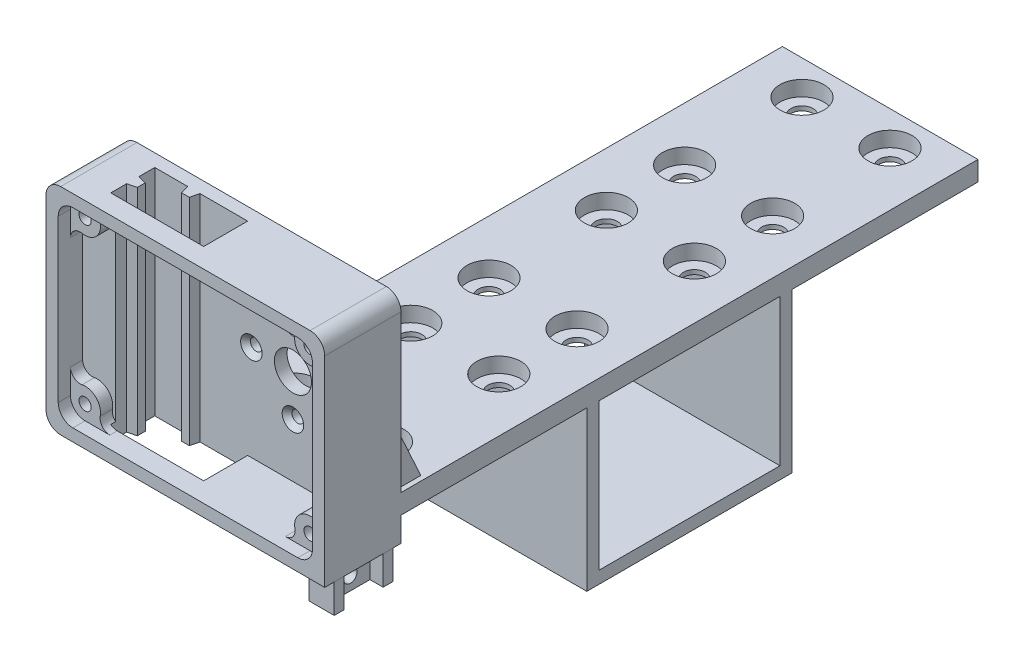
SolidWorks part; units mm, degrees
other "Markup1"
sketch "Sketch26" plane through (0, -41.85, 15.6) normal (0.2159, -0.9515, 0.2193) x (0.5478, -0.0679, -0.8339)
ref_plane "Front Plane" through (0, 0, 0) normal (0, 0, 1) x (1, 0, 0)
ref_plane "Top Plane" through (0, 0, 0) normal (0, 1, 0) x (1, 0, 0)
ref_plane "Right Plane" through (0, 0, 0) normal (1, 0, 0) x (0, 0, -1)
sketch "Sketch1" plane through (0, 0, 0) normal (1, 0, 0) x (0, 0, -1)
  line L5 (0, 0) -> (118, 0)
  line L6 (0, 0) -> (0, -4)
  line L8 (118, 0) -> (118, -4)
  line L13 (80, -4) -> (80, -36.5)
  line L14 (80, -36.5) -> (38, -36.5)
  line L15 (38, -36.5) -> (38, -4)
  line L17 (38, -4) -> (0, -4)
  line L18 (80, -4) -> (118, -4)
  line L19 (59, -36.5) -> (59, 0) construction
  line L20 (59, -4) -> (59, -34) construction
  line L25 (40.5, -4) -> (77.5, -4)
  line L26 (40.5, -4) -> (40.5, -34)
  line L27 (40.5, -34) -> (77.5, -34)
  line L28 (77.5, -4) -> (77.5, -34)
  line L29 (40.5, -19) -> (77.5, -19) construction
  dimension "D11" = 4
  dimension "D1" = 38
  dimension "D2" = 42
  dimension "D3" = 38
  dimension "D4" = 4
  dimension "D5" = 4
  dimension "D6" = 37
  dimension "D7" = 30
  dimension "D8" = 32.5
extrude "Boss-Extrude1" add sketch "Sketch1" against normal blind 40
sketch "Sketch2" plane through (0, 0, 0) normal (0, 1, 0) x (1, 0, 0)
  line L0 (-20, 116) -> (-20, 82) construction
  line L5 (-35, 19) -> (-5, 19) construction
  line L6 (-5, 36) -> (-35, 2) construction
  line L7 (-5, 116) -> (-35, 116)
  line L8 (-5, 116) -> (-5, 82)
  line L9 (-5, 82) -> (-35, 82)
  line L10 (-35, 116) -> (-35, 82)
  line L11 (-5, 116) -> (-35, 82) construction
  line L12 (-5, 82) -> (-35, 116) construction
  line L13 (-5, 76.5) -> (-35, 76.5)
  line L14 (-5, 76.5) -> (-5, 41.5)
  line L15 (-5, 41.5) -> (-35, 41.5)
  line L16 (-35, 76.5) -> (-35, 41.5)
  line L17 (-5, 76.5) -> (-35, 41.5) construction
  line L18 (-5, 41.5) -> (-35, 76.5) construction
  line L19 (-5, 2) -> (-35, 36) construction
  line L20 (-40, 0) -> (0, 0) construction
  line L21 (-40, 118) -> (0, 118) construction
  line L22 (-40, 118) -> (-40, 0) construction
  line L23 (-20, 41.5) -> (-20, 76.5) construction
  line L24 (-35, 59) -> (-5, 59) construction
  line L25 (-35, 99) -> (-5, 99) construction
  line L26 (-20, 2) -> (-20, 36) construction
  line L27 (-35, 2) -> (-35, 36)
  line L28 (-5, 36) -> (-35, 36)
  line L29 (-5, 2) -> (-5, 36)
  line L30 (-5, 2) -> (-35, 2)
  point P5 (-20, 99)
  point P10 (-20, 59)
  point P18 (-40, 59)
  point P22 (-20, 0)
  point P25 (-20, 118)
  point P29 (-11, 87)
  point P33 (-11, 111)
  point P35 (-29, 111)
  point P36 (-29, 87)
  point P40 (-29, 31)
  point P41 (-29, 7)
  point P42 (-11, 7)
  point P43 (-11, 31)
  point P44 (-20, 19)
  point P45 (-11, 71)
  point P46 (-11, 47)
  point P49 (-29, 47)
  point P50 (-29, 71)
  dimension "D1" = 35
  dimension "D2" = 30
  dimension "D3" = 5.5
  dimension "D4" = 40
  dimension "D5" = 34
  dimension "D6" = 30
  dimension "D7" = 6
  dimension "D9" = 12
  dimension "D10" = 9
sketch "Sketch3" plane through (0, 0, 0) normal (1, 0, 0) x (0, 0, -1)
  line L0 (40.5, -4) -> (77.5, -34) construction
  line L1 (77.5, -4) -> (40.5, -34) construction
  point P8 (59, -19)
hole_wizard "CBORE for M4 Pan Head Machine Screw1" positions "3DSketch1" profile "Sketch4" counterbore size "M4" standard "ANSI Metric"
sketch3d "3DSketch1"
  point P0 (-11, 0, -111)
  point P3 (-29, 0, -111)
  point P6 (-11, 0, -87)
  point P9 (-29, 0, -87)
  point P12 (-11, 0, -71)
  point P15 (-11, 0, -47)
  point P18 (-29, 0, -47)
  point P21 (-29, 0, -71)
  point P24 (-11, 0, -31)
  point P27 (-29, 0, -31)
  point P30 (-29, 0, -7)
  point P33 (-11, 0, -7)
sketch "Sketch4" plane through (-11, 0, -111) normal (1, 0, 0) x (0, 0, 1)
  line L0 (0, 0) -> (0, 4)
  line L1 (0, 4) -> (2.25, 4)
  line L3 (2.25, 4) -> (2.25, 3.1)
  line L4 (2.25, 3.1) -> (4.5, 3.1)
  line L5 (4.5, 3.1) -> (4.5, 0)
  line L7 (4.5, 0) -> (0, 0)
  line L11 (0, -6.35) -> (0, 107.95) construction
  dimension "Thru Hole Dia." = 4.5
  dimension "Thru Hole Depth" = 4
  dimension "C'Bore Dia." = 9
  dimension "C'Bore Depth" = 3.1
ref_plane "Plane1" through (-39, 0, 0) normal (1, 0, 0) x (0, 0, -1)
sketch "Sketch5" plane through (-39, 0, 0) normal (1, 0, 0) x (0, 0, -1)
  line L1 (55, -36.5) -> (63, -36.5)
  line L2 (55, -36.5) -> (55, -41.85)
  line L4 (63, -36.5) -> (63, -41.85)
  line L5 (38, -36.5) -> (80, -36.5) construction
  line L6 (63, -41.85) -> (55, -41.85)
  circle A1 centre (59, -39.5) radius 1.35
  point P4 (59, -36.5)
  point P5 (59, -36.5)
  dimension "D3" = 2.7
  dimension "D2" = 3
  dimension "D1" = 8
  dimension "D4" = 5.35
extrude "Boss-Extrude2" add sketch "Sketch5" along normal blind 3
ref_plane "Plane2" through (-28, 0, 0) normal (1, 0, 0) x (0, 0, -1)
sketch "Sketch6" plane through (-28, 0, 0) normal (1, 0, 0) x (0, 0, -1)
  line L3 (55, -36.5) -> (55, -41.85)
  line L4 (63, -41.85) -> (63, -36.5)
  line L5 (63, -36.5) -> (55, -36.5)
  line L6 (55, -36.5) -> (55, -41.85)
  line L7 (63, -41.85) -> (63, -36.5)
  line L8 (63, -36.5) -> (55, -36.5)
  line L10 (55, -41.85) -> (63, -41.85)
  line L11 (55, -41.85) -> (63, -41.85)
  circle A0 centre (59, -39.5) radius 1.35 construction
  circle A3 centre (59, -39.5) radius 1.35
  dimension "D1" = 0
extrude "Boss-Extrude3" add sketch "Sketch6" along normal blind 6
sketch "Sketch7" plane through (-28, 0, 0) normal (-1, 0, 0) x (0, 0, 1)
  line L1 (-63, -38.5) -> (-62.2, -38.5)
  line L2 (-63, -38.5) -> (-63, -40.9)
  line L3 (-63, -40.9) -> (-62.2, -40.9)
  line L4 (-62.2, -38.5) -> (-62.2, -40.9)
  line L6 (-55, -40.9) -> (-55.8, -40.9)
  line L7 (-55, -38.5) -> (-55.8, -38.5)
  line L8 (-55.8, -38.5) -> (-55.8, -40.9)
  line L9 (-55, -38.5) -> (-55, -40.9)
  line L10 (-55, -36.5) -> (-55, -41.85) construction
  line L11 (-63, -36.5) -> (-55, -36.5) construction
  line L12 (-63, -41.85) -> (-63, -36.5) construction
  dimension "D1" = 0.8
  dimension "D2" = 0.8
  dimension "D3" = 2.4
  dimension "D4" = 2.4
  dimension "D5" = 2
  dimension "D6" = 2
  dimension "D7" = 0.8
extrude "Boss-Extrude4" add sketch "Sketch7" along normal up to next
sketch "Sketch8" plane through (-36, 0, 0) normal (1, 0, 0) x (0, 0, -1)
  line L0 (63, -41.85) -> (63, -40.9) construction
  line L1 (63, -38.5) -> (62.2, -38.5)
  line L2 (63, -38.5) -> (63, -40.9)
  line L3 (63, -40.9) -> (62.2, -40.9)
  line L4 (62.2, -38.5) -> (62.2, -40.9)
  line L5 (63, -36.5) -> (55, -36.5) construction
  line L6 (55, -36.5) -> (55, -38.5) construction
  line L7 (55, -38.5) -> (55.8, -38.5)
  line L8 (55, -38.5) -> (55, -40.9)
  line L9 (55, -40.9) -> (55.8, -40.9)
  line L10 (55.8, -38.5) -> (55.8, -40.9)
  dimension "D1" = 0.8
  dimension "D2" = 2
  dimension "D3" = 2.4
  dimension "D4" = 0.8
  dimension "D5" = 2
  dimension "D6" = 2.4
ref_plane "Plane3" through (0, 0, 0) normal (0, 1, 0) x (1, 0, 0)
sketch "Sketch9" plane through (0, 0, 0) normal (0, 1, 0) x (1, 0, 0)
  line L0 (0, 40.5) -> (0, 77.5) construction
  line L1 (0, 0) -> (-57, 0)
  line L2 (0, 0) -> (0, -2.6)
  line L3 (0, -2.6) -> (-57, -2.6)
  line L4 (-57, 0) -> (-57, -2.6)
  dimension "D1" = 57
  dimension "D2" = 2.6
extrude "Boss-Extrude6" add sketch "Sketch9" along normal blind 35 and the other way blind 9
extrude "Boss-Extrude5" add sketch "Sketch8" along normal blind 2
ref_plane "Plane4" through (-37, 0, 0) normal (-1, 0, 0) x (0, 0, 1)
sketch "Sketch11" plane through (-37, 0, 0) normal (-1, 0, 0) x (0, 0, 1)
  line L0 (-0.0362, 10.9547) -> (-5.0362, 0.046)
  line L1 (22, 0) -> (-22, 0) construction
  line L2 (0, -9) -> (0, 35) construction
  line L4 (-0.0362, 10.9547) -> (-0.0362, 0.046) construction
  line L5 (-0.0362, 0.046) -> (-5.0362, 0.046) construction
  point P1 (-0.0362, 4.9009)
  point P2 (-0.0362, 10.5756)
  dimension "D1" = 12
  dimension "D2" = 5
  dimension "D3" = 0.046
  dimension "D4" = 0.0362
rib "Rib2" sketch "Sketch11" sketch "Sketch11" thickness 2 extrusion direction parallel to sketch draft on no parameters "D1"=2
ref_plane "Plane5" through (-2, 0, 0) normal (1, 0, 0) x (0, 0, -1)
sketch "Sketch12" plane through (-2, 0, 0) normal (1, 0, 0) x (0, 0, -1)
  line L0 (0.0362, 10.9547) -> (5.0362, 0.046) construction
  line L1 (0.0362, 10.9547) -> (5.0362, 0.046)
rib "Rib3" sketch "Sketch12" sketch "Sketch12" thickness 2 extrusion direction parallel to sketch draft on no parameters "D1"=2
sketch "Sketch13" plane through (0, 0, 0) normal (0, 0, -1) x (-1, 0, 0)
  line L0 (19.5, 0) -> (19.5, 35) construction
  line L1 (36, 0) -> (3, 0) construction
  line L3 (0, 35) -> (57, 35) construction
  circle A0 centre (19.5, 13) radius 3.8
  point P7 (19.5, 13)
  dimension "D2" = 7.6
  dimension "D1" = 13
extrude "Cut-Extrude1" cut sketch "Sketch13" against normal up to next
sketch "Sketch14" plane through (0, 0, 2.6) normal (0, 0, 1) x (1, 0, 0)
  line L4 (-57, -9) -> (0, -9)
  line L5 (0, -9) -> (0, 35)
  line L6 (0, 35) -> (-57, 35)
  line L7 (-57, 35) -> (-57, -9)
  line L8 (-57, -9) -> (0, -9)
  line L9 (0, -9) -> (0, 35)
  line L10 (0, 35) -> (-57, 35)
  line L11 (-57, 35) -> (-57, -9)
  dimension "D1" = 0
extrude "Boss-Extrude7" add sketch "Sketch14" along normal blind 13
sketch3d "3DSketch3"
  line L0 (-2.5, -6.5, 15.6) -> (-2.5, 32.5, 15.6)
  line L1 (-2.5, 32.5, 15.6) -> (-54.5, 32.5, 15.6)
  line L2 (-54.5, 32.5, 15.6) -> (-54.5, -6.5, 15.6)
  line L3 (-54.5, -6.5, 15.6) -> (-2.5, -6.5, 15.6)
  line L4 (-2.5, -6.5, 15.6) -> (-2.5, 32.5, 15.6)
  line L5 (-2.5, 32.5, 15.6) -> (-54.5, 32.5, 15.6)
  line L6 (-54.5, 32.5, 15.6) -> (-54.5, -6.5, 15.6)
  line L7 (-54.5, -6.5, 15.6) -> (-2.5, -6.5, 15.6)
  dimension "D1" = 2.5
extrude "Cut-Extrude2" cut sketch "3DSketch3" along direction (0, 0, 1) on the side against the normal blind 13 contours L4 L5 L6 L7
fillet "Fillet3" radius 3 7 edges at (-57, -9, 7.8) (0, 35, 7.8) (-57, 35, 7.8)
sketch "Sketch15" plane through (0, 35, 0) normal (0, 1, 0) x (1, 0, 0)
  line L20 (-31.7575, -2.6) -> (-38.2575, -2.6)
  line L21 (-38.2575, -2.6) -> (-38.7575, -4.6)
  line L22 (-38.7575, -4.6) -> (-40.7575, -4.6)
  line L23 (-40.7575, -4.6) -> (-41.2575, -2.6)
  line L24 (-41.2575, -2.6) -> (-47.7575, -2.6)
  line L25 (-47.7575, -2.6) -> (-47.7575, -5.6)
  line L26 (-47.7575, -5.6) -> (-45.7575, -6.1)
  line L27 (-45.7575, -6.1) -> (-45.7575, -8.1)
  line L28 (-45.7575, -8.1) -> (-47.7575, -8.6)
  line L29 (-47.7575, -8.6) -> (-47.7575, -10.93)
  line L30 (-47.7575, -10.93) -> (-31.7575, -10.93)
  line L31 (-31.7575, -10.93) -> (-31.7575, -2.6)
  line L32 (-31.7575, -2.6) -> (-38.2575, -2.6) construction
  line L33 (-38.2575, -2.6) -> (-38.7575, -4.6) construction
  line L34 (-38.7575, -4.6) -> (-40.7575, -4.6) construction
  line L35 (-40.7575, -4.6) -> (-41.2575, -2.6) construction
  line L36 (-41.2575, -2.6) -> (-47.7575, -2.6) construction
  line L37 (-47.7575, -2.6) -> (-47.7575, -5.6) construction
  line L38 (-47.7575, -5.6) -> (-45.7575, -6.1) construction
  line L39 (-45.7575, -6.1) -> (-45.7575, -8.1) construction
  line L40 (-45.7575, -8.1) -> (-47.7575, -8.6) construction
  line L41 (-47.7575, -8.6) -> (-47.7575, -10.93) construction
  line L42 (-47.7575, -10.93) -> (-31.7575, -10.93) construction
  line L43 (-31.7575, -10.93) -> (-31.7575, -2.6) construction
  dimension "D2" = 0
sketch3d "3DSketch4"
  line L0 (-54.5, 29.5, 2.6) -> (-54.5, -3.5, 2.6) construction
  line L1 (-54.5, 29.5, 2.6) -> (-54.5, -3.5, 2.6)
  line L2 (-51.5, 32.5, 2.6) -> (-38.5, 32.5, 2.6)
  line L3 (-38.5, 32.5, 2.6) -> (-38.5, -6.5, 2.6)
  line L4 (-38.5, -6.5, 2.6) -> (-51.5, -6.5, 2.6)
  arc A0 (-54.5, -3.5, 2.6) -> (-51.5, -6.5, 2.6) centre (-51.5, -3.5, 2.6) ccw construction
  arc A1 (-51.5, 32.5, 2.6) -> (-54.5, 29.5, 2.6) centre (-51.5, 29.5, 2.6) ccw construction
  arc A2 (-54.5, -3.5, 2.6) -> (-51.5, -6.5, 2.6) centre (-51.5, -3.5, 2.6) ccw
  arc A3 (-51.5, 32.5, 2.6) -> (-54.5, 29.5, 2.6) centre (-51.5, 29.5, 2.6) ccw
  point P3 (-51.5, -3.5, 5.6)
  point P5 (-51.5, -3.5, 5.6)
  point P8 (-51.5, 29.5, 5.6)
  point P9 (-51.5, 29.5, 5.6)
  dimension "D1" = 13
extrude "Boss-Extrude8" add sketch "3DSketch4" along direction (0, 0, -1) on the side of the normal blind 8 contours A2 L1 A3 L2 L3 L4
sketch "Sketch16" plane through (0, 35, 0) normal (0, 1, 0) x (1, 0, 0)
  line L0 (-41.2575, -2.6) -> (-47.7575, -2.6)
  line L1 (-47.7575, -2.6) -> (-47.7575, -5.85)
  line L2 (-47.7575, -5.85) -> (-46.0075, -6.2875)
  line L3 (-46.0075, -6.2875) -> (-46.0075, -7.9125)
  line L4 (-46.0075, -7.9125) -> (-47.7575, -8.35)
  line L5 (-47.7575, -8.35) -> (-47.7575, -11.6)
  line L6 (-47.7575, -11.6) -> (-28.7575, -11.6)
  line L7 (-28.7575, -11.6) -> (-28.7575, -2.6)
  line L8 (-28.7575, -2.6) -> (-38.5075, -2.6)
  line L9 (-38.5075, -2.6) -> (-38.945, -4.35)
  line L10 (-38.945, -4.35) -> (-40.57, -4.35)
  line L11 (-40.57, -4.35) -> (-41.0075, -2.6)
  line L12 (-41.0075, -2.6) -> (-41.2575, -2.6)
  line L13 (-3, 0) -> (-54, 0) construction
  line L14 (-47.7575, -8.6) -> (-47.7575, -10.93) construction
  line L17 (-45.7575, -8.1) -> (-47.7575, -8.6) construction
  line L19 (-45.7575, -6.1) -> (-45.7575, -8.1) construction
  line L21 (-38.2575, -2.6) -> (-38.7575, -4.6) construction
  dimension "D1" = 2.6
  dimension "D2" = 9
  dimension "D3" = 19
  dimension "D4" = 0.25
  dimension "D5" = 2.5
  dimension "D6" = 3.25
  dimension "D7" = 0.25
extrude "Cut-Extrude3" cut sketch "Sketch16" against normal up to next
sketch "Sketch17" plane through (0, 0, 2.6) normal (0, 0, 1) x (1, 0, 0)
  line L0 (-11, 13) -> (-28, 13) construction
  line L1 (-19.5, 4.5) -> (-19.5, 21.5) construction
  circle A0 centre (-19.5, 13) radius 3.8 construction
  point P4 (-19.5, 13)
  dimension "D1" = 17
  dimension "D2" = 17
hole_wizard "CSK for M2 Countersunk Flat Head Screw1" positions "Sketch18" profile "Sketch19" countersink size "M2" standard "ISO" end condition up to next
sketch "Sketch18" plane through (0, 0, 2.6) normal (0, 0, 1) x (1, 0, 0)
  point P0 (-19.5, 21.5)
  point P3 (-28, 13)
  point P6 (-19.5, 4.5)
  point P9 (-11, 13)
sketch "Sketch19" plane through (-19.5, 21.5, 2.6) normal (1, 0, 0) x (0, -1, 0)
  line L0 (0, 0) -> (0, 2.6)
  line L1 (0, 2.6) -> (1.2, 2.6)
  line L2 (1.2, 2.6) -> (1.2, 1)
  line L3 (1.2, 1) -> (2.2, 0)
  line L5 (2.2, 0) -> (0, 0)
  line L6 (-1.2, 1) -> (-2.2, 0) construction
  line L11 (0, -6.35) -> (0, 107.95) construction
  dimension "Thru Hole Dia." = 2.4
  dimension "Thru Hole Depth" = 2.6
  dimension "Near C'Sink Dia." = 4.4
  dimension "Near C'Sink Angle" = 90
sketch "Sketch20" plane through (0, 0, 2.6) normal (0, 0, 1) x (1, 0, 0)
  line L1 (-5.5, 32.5) -> (-28.7575, 32.5) construction
  line L2 (-2.5, -3.5) -> (-2.5, 29.5) construction
  line L3 (-6.4777, 32.5) -> (-5.5, 32.5)
  line L4 (-2.5, 28.5223) -> (-2.5, 29.5)
  arc A0 (-5.5, -6.5) -> (-2.5, -3.5) centre (-5.5, -3.5) ccw construction
  arc A1 (-2.5, 29.5) -> (-5.5, 32.5) centre (-5.5, 29.5) ccw construction
  arc A2 (-6.4777, 32.5) -> (-2.5, 28.5223) centre (-5.5, 29.5) ccw
  arc A3 (-2.5, 29.5) -> (-5.5, 32.5) centre (-5.5, 29.5) ccw construction
  arc A4 (-2.5, 29.5) -> (-5.5, 32.5) centre (-5.5, 29.5) ccw
  point P0 (-5.5, 29.5)
  point P1 (-5.5, -3.5)
  dimension "D1" = 3.1553
sketch "Sketch21" plane through (0, 0, 10.6) normal (0, 0, 1) x (1, 0, 0)
  arc A0 (-54.5, -3.5) -> (-51.5, -6.5) centre (-51.5, -3.5) ccw construction
  arc A1 (-51.5, 32.5) -> (-54.5, 29.5) centre (-51.5, 29.5) ccw construction
  point P0 (-51.5, 29.5)
  point P1 (-51.5, -3.5)
  point P2 (0, 0)
  point P6 (0, 0)
extrude "Boss-Extrude9" add sketch "Sketch20" along normal blind 10.5
fillet "Fillet4" radius 2 2 edges at (-2.5, 28.5223, 7.85) (-6.4777, 32.5, 7.85)
sketch "Sketch22" plane through (0, 0, 15.6) normal (0, 0, 1) x (1, 0, 0)
  line L0 (-28.5, -6.5) -> (-28.5, 32.5) construction
  line L2 (-54.5, 13) -> (-2.5, 13) construction
  line L12 (-5.5, 32.5) -> (-51.5, 32.5) construction
  line L13 (-51.5, -6.5) -> (-5.5, -6.5) construction
  line L15 (-54.5, 29.5) -> (-54.5, -3.5) construction
  line L16 (-2.5, -3.5) -> (-2.5, 29.5) construction
  point P2 (0, 0)
  point P3 (0, 0)
  point P4 (0, 0)
  point P7 (0, 0)
  point P8 (0, 0)
  point P9 (0, 0)
  point P10 (0, 0)
  point P11 (0, 0)
  point P12 (-53.1765, 13)
  point P14 (0, 0)
  point P15 (0, 0)
  point P16 (0, 0)
  point P17 (0, 0)
  point P18 (0, 0)
  point P19 (0, 0)
  point P22 (0, 0)
  point P23 (0, 0)
  point P24 (0, 0)
  point P25 (0, 0)
  point P26 (0, 0)
  point P28 (0, 0)
  point P29 (0, 0)
  point P30 (0, 0)
  point P33 (0, 0)
  point P34 (0, 0)
  point P35 (0, 0)
  point P36 (0, 0)
  point P37 (0, 0)
ref_plane "Plane7" through (0, 13, 0) normal (0, -1, 0) x (1, 0, 0)
ref_plane "Plane8" through (-28.5, 0, 0) normal (1, 0, 0) x (0, 0, -1)
mirror "Mirror1" about plane through (-28.5, 0, 0) normal (1, 0, 0) of "Boss-Extrude9"
mirror "Mirror2" about plane through (0, 13, 0) normal (0, -1, 0) of "Mirror1", "Boss-Extrude9"
fillet "Fillet5" radius 2 6 edges at (-50.5223, 32.5, 11.85) (-6.4777, -6.5, 7.85) (-2.5, -2.5223, 7.85) (-50.5223, -6.5, 11.85) (-54.5, -2.5223, 11.85) (-54.5, 28.5223, 11.85)
hole_wizard "M3 Tapped Hole1" positions "Sketch23" profile "Sketch25" tap size "M3" standard "ISO"
sketch "Sketch23" plane through (0, 0, 13.1) normal (0, 0, 1) x (1, 0, 0)
  point P0 (-5.5, -3.5)
  point P3 (-51.5, 29.5)
  point P6 (-51.5, -3.5)
  point P9 (-5.5, 29.5)
sketch "Sketch25" plane through (-5.5, -3.5, 13.1) normal (1, 0, 0) x (0, -1, 0)
  line L0 (0, 0) -> (0, 10.7511)
  line L1 (0, 10.7511) -> (1.25, 10)
  line L2 (1.25, 10) -> (1.25, 0)
  line L5 (1.25, 0) -> (0, 0)
  line L10 (0, 10.7511) -> (-1.25, 10) construction
  line L11 (0, -6.35) -> (0, 107.95) construction
  dimension "Tap Drill Dia." = 2.5
  dimension "Tap Drill Depth" = 10
  dimension "Drill Angle" = 118
cosmetic thread "Hole Thread1" parameters "D1"=6, "D2"=3
cosmetic thread "Hole Thread2" parameters "D1"=6, "D2"=3
cosmetic thread "Hole Thread3" parameters "D1"=6, "D2"=3
cosmetic thread "Hole Thread4" parameters "D1"=6, "D2"=3
sketch "Sketch27" plane through (0, -9, 0) normal (0, -1, 0) x (1, 0, 0)
  line L0 (-28.7575, 11.6) -> (-28.7575, 2.6) construction
  line L2 (-5.2575, 13.6) -> (-5.2575, 1.6)
  line L3 (-5.2575, 1.6) -> (-0.0575, 1.6)
  line L7 (-2.7575, 3.6) -> (-0.0575, 3.6)
  line L8 (-2.7575, 3.6) -> (-2.7575, 11.6)
  line L9 (-2.7575, 11.6) -> (-0.0575, 11.6)
  line L10 (-0.0575, 13.6) -> (-0.0575, 11.6)
  line L12 (-0.0575, 3.6) -> (-0.0575, 1.6)
  line L13 (-5.2575, 13.6) -> (-0.0575, 13.6)
  line L16 (-54, 15.6) -> (0, 15.6) construction
  point P1 (-0.7575, 11.6)
  point P3 (-6.7575, 13.57)
  point P12 (-4.2575, 3.6251)
  point P13 (0, 0)
  point P14 (0, 0)
  point P15 (-4.2575, 11.6)
  point P18 (-10.7575, 3.6)
  point P19 (0, 0)
  point P20 (0, 0)
  point P21 (-14.2575, 3.6)
  point P22 (0, 0)
  dimension "D1" = 23.5
  dimension "D2" = 12
  dimension "D3" = 5.2
  dimension "D4" = 2
  dimension "D5" = 8
  dimension "D6" = 2
  dimension "D7" = 2.5
extrude "Boss-Extrude10" add sketch "Sketch27" along normal blind 6 contours L8 L9 L10 L13 L2 L3 L12 L7
sketch "Sketch30" plane through (-5.2575, 0, 0) normal (-1, 0, 0) x (0, 0, 1)
  line L0 (13.6, -15) -> (1.6, -15) construction
  line L1 (1.6, -15) -> (1.6, -9) construction
  circle A0 centre (7.6, -12.3) radius 1.35
  dimension "D1" = 2.7
  dimension "D2" = 2.7
  dimension "D3" = 6
extrude "Cut-Extrude5" cut sketch "Sketch30" against normal up to next
sketch "Sketch31" plane through (-57, 0, 0) normal (-1, 0, 0) x (0, 0, 1)
  line L0 (0, -6) -> (0, 32) construction
  line L2 (15.6, 32) -> (0, 32) construction
  circle A0 centre (4.5, 25) radius 1.3
  point P6 (5.4751, 32)
  point P7 (4.4868, 31.794)
  point P10 (4.5346, 28.9036)
  dimension "D1" = 2.6
  dimension "D2" = 4.5
  dimension "D3" = 7
extrude "Cut-Extrude6" cut sketch "Sketch31" against normal blind 7
fillet "Fillet6" radius 2 1 edges at (-5.2575, -9, 7.6)
sketch "Sketch36" plane through (0, 0, 0) normal (0, 0, -1) x (-1, 0, 0)
  line L0 (45.3535, -5.4921) -> (40.4535, -5.4921) construction
  line L1 (40.4535, -5.4921) -> (40.4535, -8.9921) construction
  line L2 (40.4535, -8.9921) -> (53.3535, -8.9921) construction
  line L3 (53.3535, -8.9921) -> (53.3535, -5.4921) construction
  line L4 (53.3535, -5.4921) -> (48.4535, -5.4921) construction
  line L5 (48.4535, -5.4921) -> (48.4535, -3.4921) construction
  line L6 (48.4535, -3.4921) -> (45.3535, -3.4921) construction
  line L7 (45.3535, -3.4921) -> (45.3535, -5.4921) construction
  line L8 (40.4535, -5.4921) -> (45.1535, -5.4921) construction
  line L9 (45.1535, -5.4921) -> (45.1535, -3.2921) construction
  line L10 (45.1535, -3.2921) -> (48.6535, -3.2921) construction
  line L11 (48.6535, -3.2921) -> (48.6535, -5.4921) construction
  line L12 (48.6535, -5.4921) -> (53.3535, -5.4921) construction
  line L13 (53.3535, -5.4921) -> (53.3535, -3.0921) construction
  line L14 (53.3535, -3.0921) -> (51.8535, -3.0921) construction
  line L15 (51.8535, -3.0921) -> (51.1535, -2.3921) construction
  line L16 (51.1535, -2.3921) -> (49.1535, -2.3921) construction
  line L17 (49.1535, -2.3921) -> (48.4535, -3.0921) construction
  line L18 (48.4535, -3.0921) -> (45.3535, -3.0921) construction
  line L19 (45.3535, -3.0921) -> (44.6535, -2.3921) construction
  line L20 (44.6535, -2.3921) -> (42.6535, -2.3921) construction
  line L21 (42.6535, -2.3921) -> (41.9535, -3.0921) construction
  line L22 (41.9535, -3.0921) -> (40.4535, -3.0921) construction
  line L23 (40.4535, -3.0921) -> (40.4535, -5.4921) construction
  line L24 (47.7575, 170.5667) -> (47.7575, -89.4333) construction
  line L25 (45.3535, -5.4921) -> (40.4535, -5.4921)
  line L26 (40.4535, -5.4921) -> (40.4535, -8.9921)
  line L27 (40.4535, -8.9921) -> (53.3535, -8.9921)
  line L28 (53.3535, -8.9921) -> (53.3535, -5.4921)
  line L29 (53.3535, -5.4921) -> (48.4535, -5.4921)
  line L30 (48.4535, -5.4921) -> (48.4535, -3.4921)
  line L31 (48.4535, -3.4921) -> (45.3535, -3.4921)
  line L32 (45.3535, -3.4921) -> (45.3535, -5.4921)
  line L33 (40.4535, -5.4921) -> (45.1535, -5.4921)
  line L34 (45.1535, -5.4921) -> (45.1535, -3.2921)
  line L35 (45.1535, -3.2921) -> (48.6535, -3.2921)
  line L36 (48.6535, -3.2921) -> (48.6535, -5.4921)
  line L37 (48.6535, -5.4921) -> (53.3535, -5.4921)
  line L38 (53.3535, -5.4921) -> (53.3535, -3.0921)
  line L39 (53.3535, -3.0921) -> (51.8535, -3.0921)
  line L40 (51.8535, -3.0921) -> (51.1535, -2.3921)
  line L41 (51.1535, -2.3921) -> (49.1535, -2.3921)
  line L42 (49.1535, -2.3921) -> (48.4535, -3.0921)
  line L43 (48.4535, -3.0921) -> (45.3535, -3.0921)
  line L44 (45.3535, -3.0921) -> (44.6535, -2.3921)
  line L45 (44.6535, -2.3921) -> (42.6535, -2.3921)
  line L46 (42.6535, -2.3921) -> (41.9535, -3.0921)
  line L47 (41.9535, -3.0921) -> (40.4535, -3.0921)
  line L48 (40.4535, -3.0921) -> (40.4535, -5.4921)
  line L49 (47.7575, 170.5667) -> (47.7575, -89.4333)
  arc A0 (42.6535, -3.8921) -> (44.6535, -3.8921) centre (43.6535, -3.8921) ccw construction
  arc A1 (44.6535, -3.8921) -> (42.6535, -3.8921) centre (43.6535, -3.8921) ccw construction
  arc A2 (49.1535, -3.8921) -> (51.1535, -3.8921) centre (50.1535, -3.8921) ccw construction
  arc A3 (51.1535, -3.8921) -> (49.1535, -3.8921) centre (50.1535, -3.8921) ccw construction
  arc A4 (42.6535, -3.8921) -> (44.6535, -3.8921) centre (43.6535, -3.8921) ccw
  arc A5 (44.6535, -3.8921) -> (42.6535, -3.8921) centre (43.6535, -3.8921) ccw
  arc A6 (49.1535, -3.8921) -> (51.1535, -3.8921) centre (50.1535, -3.8921) ccw
  arc A7 (51.1535, -3.8921) -> (49.1535, -3.8921) centre (50.1535, -3.8921) ccw
sketch "Sketch37" plane through (0, 0, 0) normal (0, 0, -1) x (-1, 0, 0)
  circle A0 centre (50.1535, -3.8921) radius 0.9
  circle A1 centre (43.6535, -3.8921) radius 0.9
  point P4 (0, 0)
  point P5 (43.8389, -4.767)
  point P8 (0, 0)
  dimension "D1" = 1.8
  dimension "D2" = 1.8
extrude "Boss-Extrude12" add sketch "Sketch37" along normal blind 6 draft 1 separate body
ref_plane "Plane9" through (0, -5.4921, 0) normal (0, 1, 0) x (1, 0, 0)
